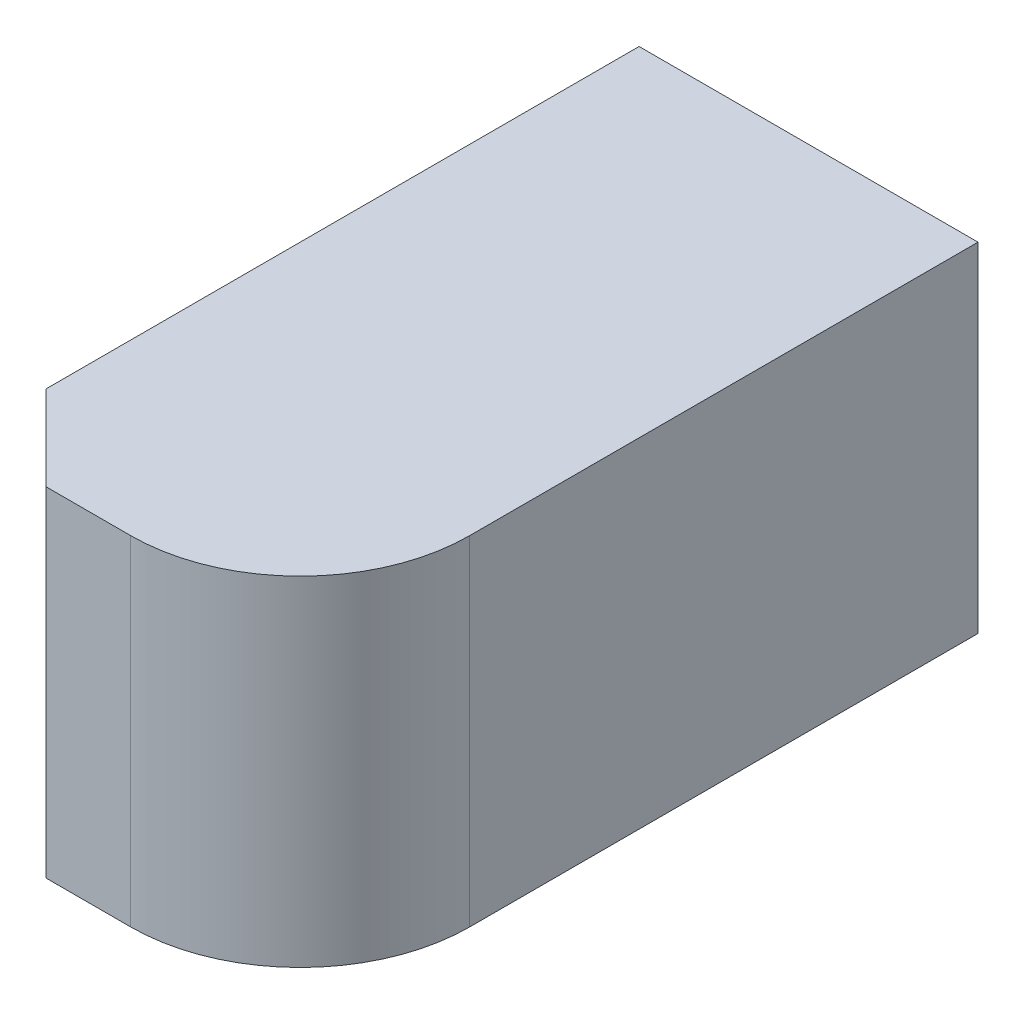
SolidWorks part; units mm, degrees
ref_plane "Front Plane" through (0, 0, 0) normal (0, 0, 1) x (1, 0, 0)
ref_plane "Top Plane" through (0, 0, 0) normal (0, 1, 0) x (1, 0, 0)
ref_plane "Right Plane" through (0, 0, 0) normal (1, 0, 0) x (0, 0, -1)
sketch "Sketch2" plane through (0, 0, 0) normal (0, 1, 0) x (1, 0, 0)
  line L1 (0, 0) -> (20, 0)
  line L2 (0, 0) -> (0, 40)
  line L3 (0, 40) -> (20, 40)
  line L4 (20, 0) -> (20, 40)
  line L5 (0, 0) -> (20, 40) construction
  line L6 (0, 40) -> (20, 0) construction
  point P4 (10, 20)
  dimension "D1" = 20
  dimension "D2" = 40
extrude "Boss-Extrude1" add sketch "Sketch2" along normal blind 20
fillet "Fillet1" radius 10 1 edges at (20, 10, 0)
chamfer "Chamfer1" distance 5 angle 45 1 edges at (0, 10, 0)
